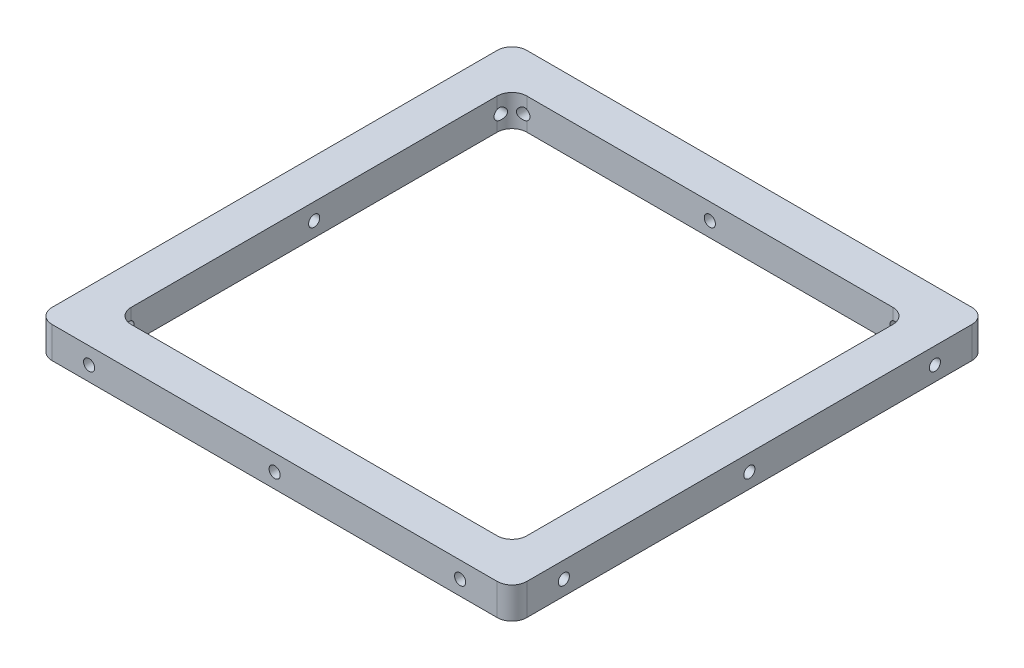
SolidWorks part; units mm, degrees
material "6061-T6 (SS)"
ref_plane "Front Plane" through (0, 0, 0) normal (0, 0, 1) x (1, 0, 0)
ref_plane "Top Plane" through (0, 0, 0) normal (0, 1, 0) x (1, 0, 0)
ref_plane "Right Plane" through (0, 0, 0) normal (1, 0, 0) x (0, 0, -1)
sketch "Sketch1" plane through (0, 0, 0) normal (0, 1, 0) x (1, 0, 0)
  line L0 (-40.05, -40.05) -> (-40.05, 40.05)
  line L1 (48.05, -48.05) -> (-48.05, -48.05)
  line L2 (48.05, -48.05) -> (48.05, 48.05)
  line L3 (48.05, 48.05) -> (-48.05, 48.05)
  line L4 (-48.05, -48.05) -> (-48.05, 48.05)
  line L5 (48.05, -48.05) -> (-48.05, 48.05) construction
  line L6 (48.05, 48.05) -> (-48.05, -48.05) construction
  line L7 (40.05, 40.05) -> (-40.05, 40.05)
  line L8 (40.05, -40.05) -> (40.05, 40.05)
  line L9 (40.05, -40.05) -> (-40.05, -40.05)
  point P0 (0, 0)
  dimension "D1" = 96.1
  dimension "D2" = 96.1
  dimension "D3" = 8
extrude "Boss-Extrude1" add sketch "Sketch1" along normal blind 6.35
fillet "Fillet1" radius 3 8 edges at (-40.05, 3.175, -40.05) (40.05, 3.175, -40.05) (40.05, 3.175, 40.05) (-40.05, 3.175, 40.05) (-48.05, 3.175, -48.05) (48.05, 3.175, -48.05) (48.05, 3.175, 48.05) (-48.05, 3.175, 48.05)
hole_wizard "#43 (0.089) Diameter Hole1" positions "Sketch3" profile "Sketch2" hole size "#43" standard "ANSI Inch" end condition through all
sketch "Sketch3" plane through (0, 0, -48.05) normal (0, 0, -1) x (-1, 0, 0)
  line L2 (-45.05, 0) -> (45.05, 0) construction
  line L3 (0, 0) -> (0, 6.35) construction
  line L4 (-45.05, 6.35) -> (45.05, 6.35) construction
  line L5 (45.05, 0) -> (45.05, 6.35) construction
  line L6 (-45.05, 6.35) -> (-45.05, 0) construction
  point P0 (0, 3)
  point P19 (-37.55, 3)
  point P21 (37.55, 3)
  dimension "D1" = 3
  dimension "D2" = 7.5
  dimension "D3" = 7.5
  dimension "D4" = 3
  dimension "D5" = 3
sketch "Sketch2" plane through (0, 3, -48.05) normal (1, 0, 0) x (0, 1, 0)
  line L0 (0, 0) -> (0, 96.1)
  line L1 (0, 96.1) -> (1.1303, 96.1)
  line L2 (1.1303, 96.1) -> (1.1303, 0)
  line L5 (1.1303, 0) -> (0, 0)
  line L11 (0, -6.35) -> (0, 107.95) construction
  dimension "Thru Hole Dia." = 2.2606
  dimension "Thru Hole Depth" = 96.1
hole_wizard "#43 (0.089) Diameter Hole2" positions "Sketch5" profile "Sketch4" hole size "#43" standard "ANSI Inch" end condition through all
sketch "Sketch5" plane through (-48.05, 0, 0) normal (-1, 0, 0) x (0, 0, 1)
  line L0 (0, 0) -> (0, 6.35) construction
  line L1 (-45.05, 0) -> (45.05, 0) construction
  line L2 (-45.05, 6.35) -> (45.05, 6.35) construction
  line L3 (45.05, 0) -> (45.05, 6.35) construction
  line L4 (-45.05, 6.35) -> (-45.05, 0) construction
  point P0 (0, 3)
  point P15 (-37.55, 3)
  point P17 (37.55, 3)
  dimension "D1" = 7.5
  dimension "D2" = 7.5
  dimension "D3" = 3
  dimension "D4" = 3
  dimension "D5" = 3
sketch "Sketch4" plane through (-48.05, 3, 0) normal (0, 1, 0) x (0, 0, 1)
  line L0 (0, 0) -> (0, 96.1)
  line L1 (0, 96.1) -> (1.1303, 96.1)
  line L2 (1.1303, 96.1) -> (1.1303, 0)
  line L5 (1.1303, 0) -> (0, 0)
  line L11 (0, -6.35) -> (0, 107.95) construction
  dimension "Thru Hole Dia." = 2.2606
  dimension "Thru Hole Depth" = 96.1
